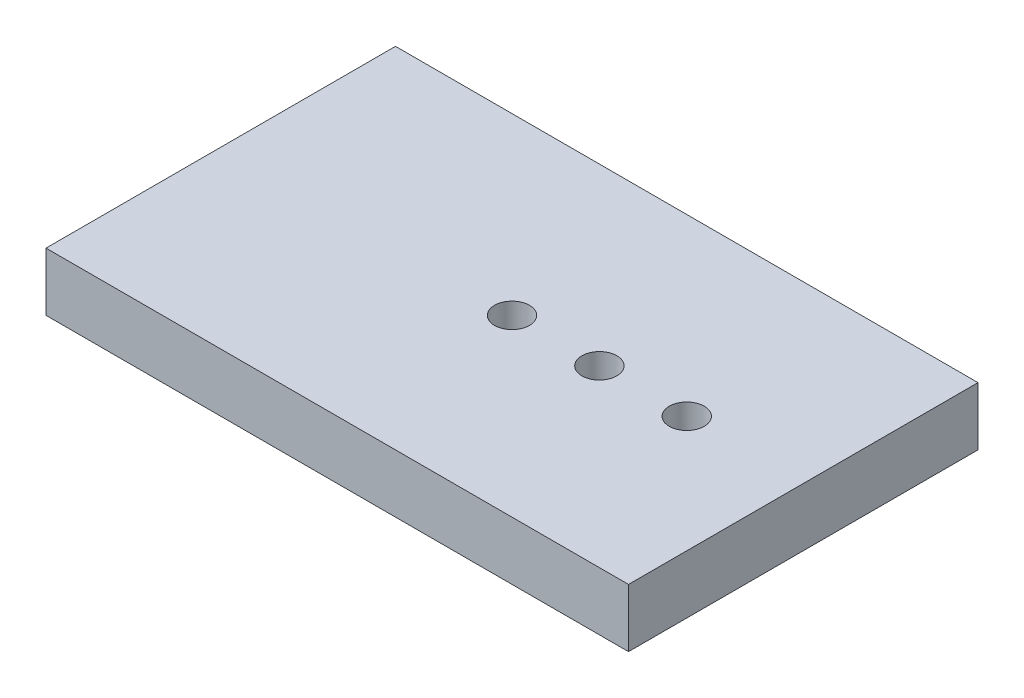
SolidWorks part; units mm, degrees
ref_plane "前视基准面" through (0, 0, 0) normal (0, 0, 1) x (1, 0, 0)
ref_plane "上视基准面" through (0, 0, 0) normal (0, 1, 0) x (1, 0, 0)
ref_plane "右视基准面" through (0, 0, 0) normal (1, 0, 0) x (0, 0, -1)
other "Configuration Table"
sketch "草图1" plane through (0, 0, 0) normal (0, 1, 0) x (1, 0, 0)
  line L1 (-50, -30) -> (50, -30)
  line L2 (-50, -30) -> (-50, 30)
  line L3 (-50, 30) -> (50, 30)
  line L4 (50, -30) -> (50, 30)
  line L5 (0, 30) -> (0, -30) construction
  line L6 (-50, 0) -> (50, 0) construction
  point P0 (0, 0)
extrude "凸台-拉伸1" add sketch "草图1" along normal blind 10
sketch "草图2" plane through (0, 0, 0) normal (0, 1, 0) x (1, 0, 0)
  circle A0 centre (30, 0) radius 3
extrude "切除-拉伸1" cut sketch "草图2" along normal blind 20
pattern_linear "阵列(线性)1" count 3 spacing 15 along (-1, 0, 0) of "切除-拉伸1"
